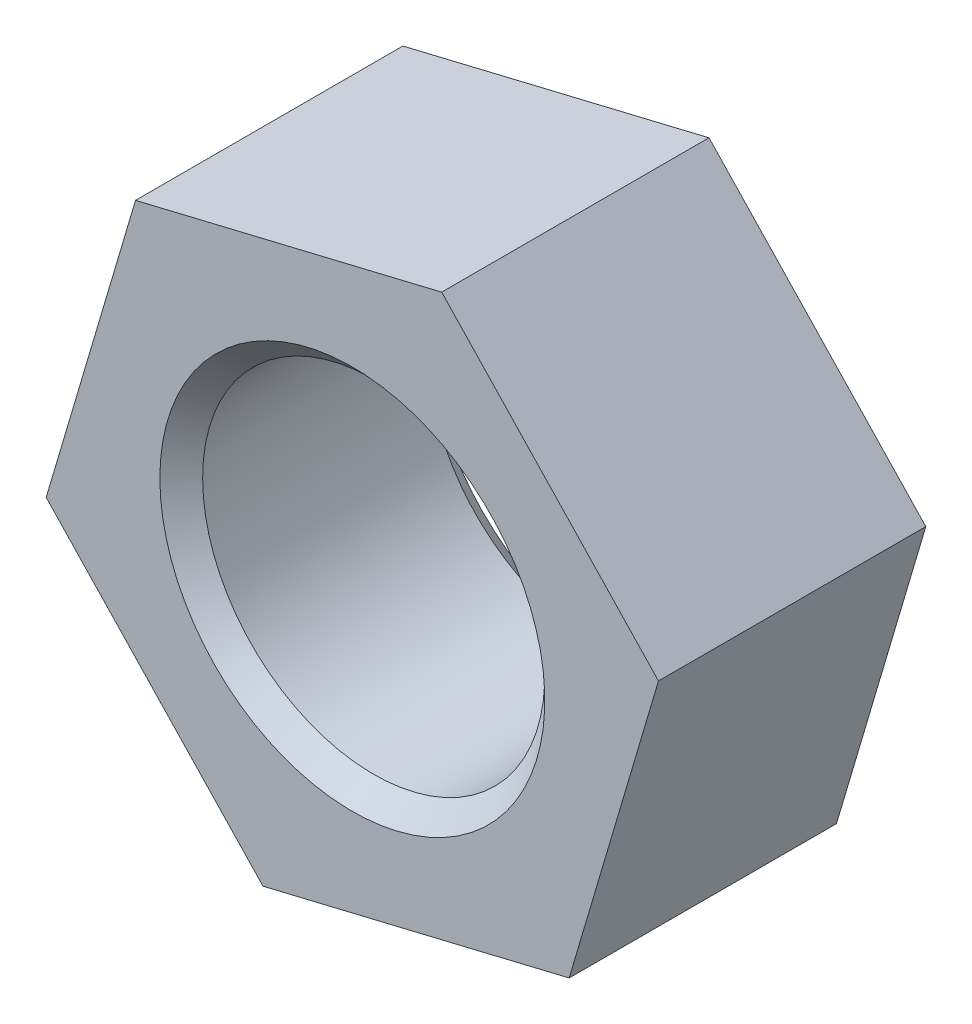
SolidWorks part; units mm, degrees
ref_plane "Front Plane" through (0, 0, 0) normal (0, 0, 1) x (1, 0, 0)
ref_plane "Top Plane" through (0, 0, 0) normal (0, 1, 0) x (1, 0, 0)
ref_plane "Right Plane" through (0, 0, 0) normal (1, 0, 0) x (0, 0, -1)
sketch "Sketch1" plane through (0, 0, 0) normal (0, 0, 1) x (1, 0, 0)
  line L0 (0, 0) -> (0, 3.85) construction
  line L2 (0, 0) -> (0, -3.85) construction
  line L3 (-5.0686, 5.3382) -> (-7.1573, -1.7204)
  line L4 (-7.1573, -1.7204) -> (-2.0887, -7.0587)
  line L5 (-2.0887, -7.0587) -> (5.0686, -5.3382)
  line L6 (5.0686, -5.3382) -> (7.1573, 1.7204)
  line L7 (7.1573, 1.7204) -> (2.0887, 7.0587)
  line L8 (2.0887, 7.0587) -> (-5.0686, 5.3382)
  circle A0 centre (0, 0) radius 4
  circle A1 centre (0, 0) radius 6.375 construction
  dimension "D1" = 12.75
  dimension "THREAD SIZE" = 8
extrude "NUT" add sketch "Sketch1" along normal blind 6.25
chamfer "Chanfrein1" distance 0.5 angle 45 2 edges at (4, 0, 6.25) (4, 0, 0)
